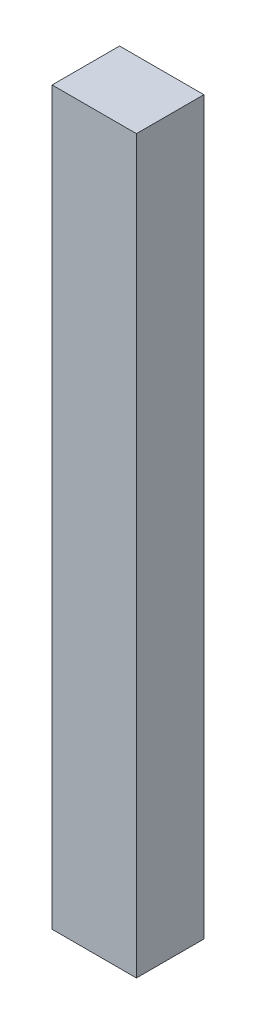
SolidWorks part; units mm, degrees
ref_plane "Plan de face" through (0, 0, 0) normal (0, 0, 1) x (1, 0, 0)
ref_plane "Plan de dessus" through (0, 0, 0) normal (0, 1, 0) x (1, 0, 0)
ref_plane "Plan de droite" through (0, 0, 0) normal (1, 0, 0) x (0, 0, -1)
sketch "Esquisse1" plane through (0, 0, 0) normal (0, 0, 1) x (1, 0, 0)
  line L1 (-268.4317, -386.4296) -> (-218.4317, -386.4296)
  line L2 (-268.4317, -386.4296) -> (-268.4317, -820)
  line L3 (-268.4317, -820) -> (-218.4317, -820)
  line L4 (-218.4317, -386.4296) -> (-218.4317, -820)
  dimension "D1" = 50
extrude "Boss.-Extru.1" add sketch "Esquisse1" along normal blind 40
